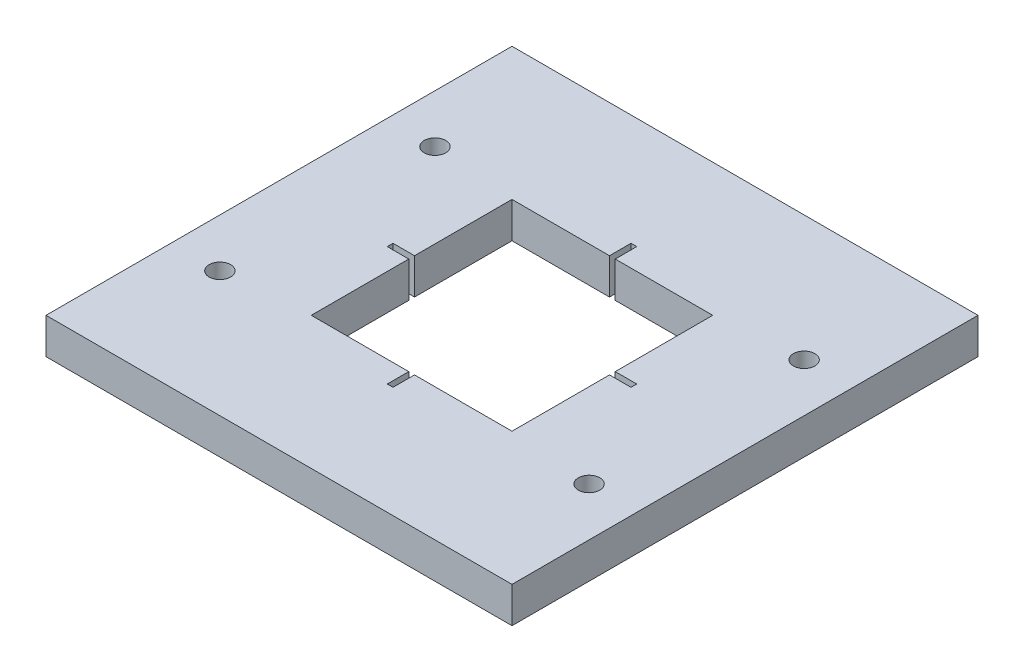
SolidWorks part; units mm, degrees
ref_plane "Alzado" through (0, 0, 0) normal (0, 0, 1) x (1, 0, 0)
ref_plane "Planta" through (0, 0, 0) normal (0, 1, 0) x (1, 0, 0)
ref_plane "Vista lateral" through (0, 0, 0) normal (1, 0, 0) x (0, 0, -1)
sketch "Croquis1" plane through (0, 0, 0) normal (0, 1, 0) x (1, 0, 0)
  line L0 (0, 0) -> (55, 55) construction
  line L1 (0, 0) -> (55, 0)
  line L2 (0, 0) -> (0, 55)
  line L3 (0, 55) -> (55, 55)
  line L4 (55, 0) -> (55, 55)
  line L5 (1.75, 0) -> (1.75, 55) construction
  line L6 (13.5, 13.5) -> (27.1, 13.5)
  line L7 (13.5, 13.5) -> (13.5, 27.1)
  line L8 (13.5, 41.5) -> (27.1, 41.5)
  line L9 (41.5, 13.5) -> (41.5, 27.1)
  line L10 (13.5, 13.5) -> (41.5, 41.5) construction
  line L11 (13.5, 41.5) -> (41.5, 13.5) construction
  line L12 (27.5, 0) -> (27.5, 55) construction
  line L13 (3.5, 0) -> (3.5, 55) construction
  line L14 (3.5, 27.5) -> (0, 27.5) construction
  line L15 (3.25, 42.5) -> (3.25, 27.5) construction
  line L16 (3.25, 27.5) -> (3.25, 12.5) construction
  line L17 (0, 27.5) -> (55, 27.5) construction
  line L18 (27.1, 44.5) -> (27.9, 44.5)
  line L19 (27.1, 44.5) -> (27.1, 41.5)
  line L21 (27.9, 44.5) -> (27.9, 41.5)
  line L22 (27.1, 44.5) -> (27.9, 41.5) construction
  line L23 (27.1, 41.5) -> (27.9, 44.5) construction
  line L25 (44.5, 27.9) -> (41.5, 27.9)
  line L26 (44.5, 27.9) -> (44.5, 27.1)
  line L27 (44.5, 27.1) -> (41.5, 27.1)
  line L29 (44.5, 27.9) -> (41.5, 27.1) construction
  line L30 (44.5, 27.1) -> (41.5, 27.9) construction
  line L31 (27.9, 10.5) -> (27.9, 13.5)
  line L32 (27.1, 10.5) -> (27.1, 13.5)
  line L33 (27.1, 10.5) -> (27.9, 10.5)
  line L34 (10.5, 27.1) -> (13.5, 27.1)
  line L36 (10.5, 27.9) -> (13.5, 27.9)
  line L37 (10.5, 27.9) -> (10.5, 27.1)
  line L38 (41.5, 27.9) -> (41.5, 41.5)
  line L39 (27.9, 13.5) -> (41.5, 13.5)
  line L40 (13.5, 27.9) -> (13.5, 41.5)
  line L41 (27.9, 41.5) -> (41.5, 41.5)
  circle A0 centre (1.75, 42.5) radius 1.5
  circle A1 centre (1.75, 12.5) radius 1.5
  circle A2 centre (53.25, 42.5) radius 1.5
  circle A3 centre (53.25, 12.5) radius 1.5
  point P4 (27.5, 27.5)
  point P18 (1.75, 27.5)
  point P25 (27.5, 43)
  point P35 (43, 27.5)
  dimension "D4" = 3
  dimension "D1" = 55
  dimension "D2" = 28
  dimension "D3" = 24
  dimension "D5" = 15
  dimension "D6" = 0.8
  dimension "D7" = 3
extrude "Saliente-Extruir1" add sketch "Croquis1" along normal blind 5
sketch "Croquis2" plane through (0, 5, 0) normal (0, 1, 0) x (1, 0, 0)
  line L0 (27.5, 55) -> (27.5, 60) construction
  line L1 (-5, -5) -> (60, -5)
  line L2 (-5, -5) -> (-5, 60)
  line L3 (-5, 60) -> (60, 60)
  line L4 (0, 55) -> (0, 0)
  line L5 (0, 0) -> (55, 0)
  line L6 (55, 0) -> (55, 55)
  line L7 (55, 55) -> (0, 55)
  line L8 (0, 55) -> (0, 0)
  line L9 (0, 0) -> (55, 0)
  line L10 (55, 0) -> (55, 55)
  line L11 (55, 55) -> (0, 55)
  line L12 (60, -5) -> (60, 60)
  line L13 (55, 27.5) -> (60, 27.5) construction
  dimension "D2" = 65
  dimension "D1" = 0
extrude "Saliente-Extruir2" add sketch "Croquis2" against normal blind 5
